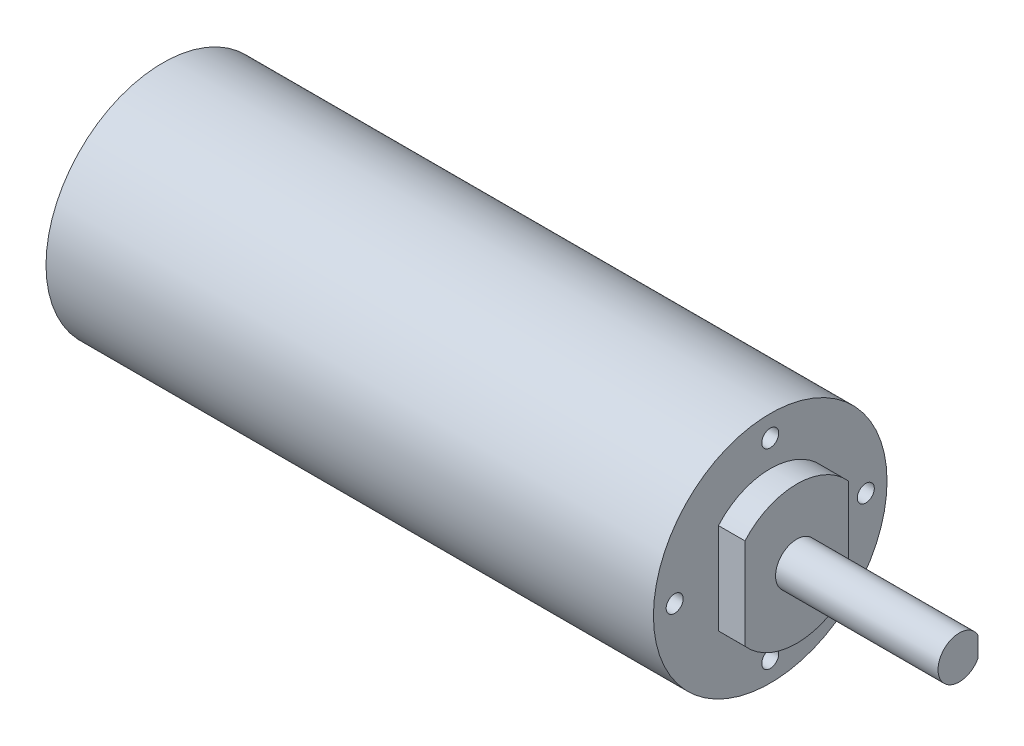
SolidWorks part; units mm, degrees
ref_plane "Front Plane" through (0, 0, 0) normal (0, 0, 1) x (1, 0, 0)
ref_plane "Top Plane" through (0, 0, 0) normal (0, 1, 0) x (1, 0, 0)
ref_plane "Right Plane" through (0, 0, 0) normal (1, 0, 0) x (0, 0, -1)
sketch "Sketch1" plane through (0, 0, 0) normal (1, 0, 0) x (0, 0, -1)
  circle A0 centre (0, 0) radius 11
extrude "Boss-Extrude1" add sketch "Sketch1" along normal blind 57.2
sketch "Sketch2" plane through (57.2, 0, 0) normal (1, 0, 0) x (0, 0, -1)
  line L0 (12.1, 0) -> (-12.1, 0) construction
  line L1 (0, 12.1) -> (0, -12.1) construction
  point P0 (9, 0)
  point P1 (0, 9)
  point P4 (-9, 0)
  point P7 (0, -9)
hole_wizard "Tap Drill for M2x0.4 Tap1" positions "Sketch2" profile "Sketch3" hole size "M2x0.4" standard "ANSI Metric"
sketch "Sketch3" plane through (57.2, 0, -9) normal (0, 1, 0) x (0, 0, -1)
  line L0 (0, 0) -> (0, 4.4807)
  line L1 (0, 4.4807) -> (0.8, 4)
  line L2 (0.8, 4) -> (0.8, 0)
  line L5 (0.8, 0) -> (0, 0)
  line L10 (0, 4.4807) -> (-0.8, 4) construction
  line L11 (0, -6.35) -> (0, 107.95) construction
  dimension "Hole Dia." = 1.6
  dimension "Hole Depth" = 4
  dimension "Drill Angle" = 118
sketch "Sketch4" plane through (57.2, 0, 0) normal (1, 0, 0) x (0, 0, -1)
  line L0 (5.6479, 3.2173) -> (5.5429, 3.395)
  line L1 (-4.8776, 4.2964) -> (-4.8776, -4.2964)
  line L2 (0, 12.1) -> (0, -12.1) construction
  line L3 (4.8776, 4.2964) -> (4.8776, -4.2964)
  circle A0 centre (0, 0) radius 6.5
extrude "Boss-Extrude2" add sketch "Sketch4" along normal blind 2.5 contours L3 A0 L1
sketch "Sketch5" plane through (59.7, 0, 0) normal (1, 0, 0) x (0, 0, -1)
  line L0 (1.7651, 0.9404) -> (1.7651, -0.9404)
  circle A0 centre (0, 0) radius 2
extrude "Boss-Extrude3" add sketch "Sketch5" along normal blind 15.3 contours L0 A0
